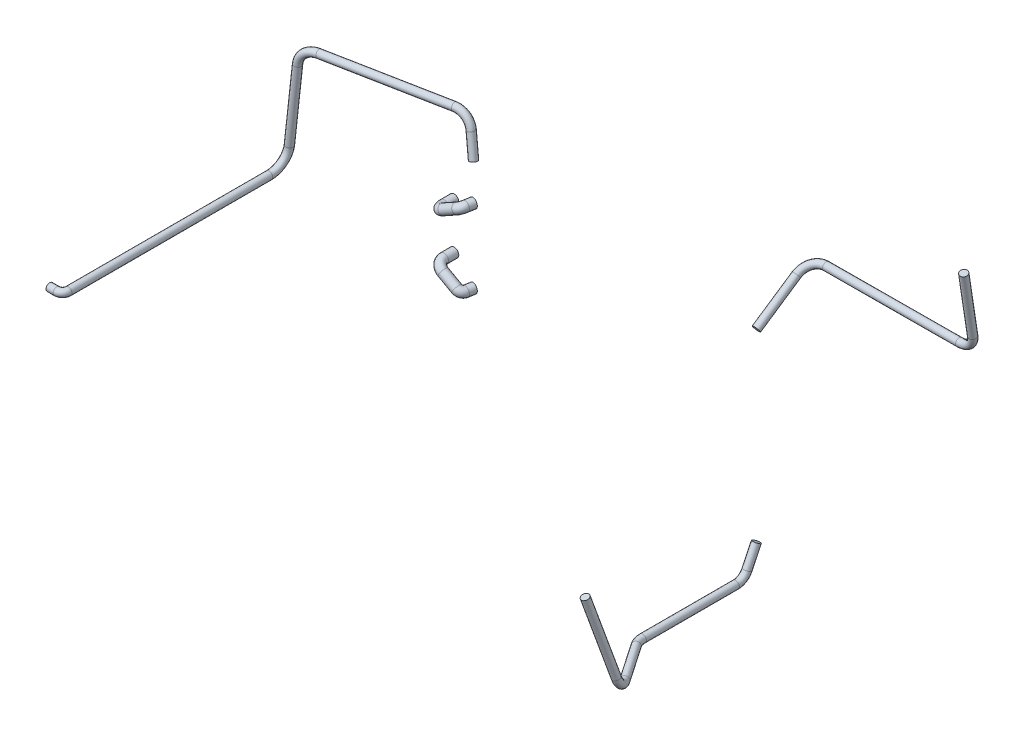
SolidWorks part; units mm, degrees
material "PVC Rigid"
ref_plane "Front Plane" through (0, 0, 0) normal (0, 0, 1) x (1, 0, 0)
ref_plane "Top Plane" through (0, 0, 0) normal (0, 1, 0) x (1, 0, 0)
ref_plane "Right Plane" through (0, 0, 0) normal (1, 0, 0) x (0, 0, -1)
sketch3d "Pipe path 1"
  line L0 (300, 25, 337) -> (300, 25, 348)
  line L1 (307.8674, 29.3708, 357) -> (322.8592, 37.6996, 357)
  line L2 (327.7787, 40, 352.3275) -> (329, 40, 345)
  arc A0 (300, 25, 348) -> (307.8674, 29.3708, 357) centre (307.8674, 29.3708, 348) ccw
  arc A1 (322.8592, 37.6996, 357) -> (327.7787, 40, 352.3275) centre (323.0737, 37.3135, 351.5434) ccw
  point P6 (300, 25, 357)
  point P7 (303.4966, 37.2382, 348)
  point P10 (327, 40, 357)
  point P11 (320.4237, 42.0834, 351.1017)
  dimension "D1" = 9
  dimension "D2" = 5.4745
sweep "Pipe 1" add path "Pipe path 1" circular profile diameter 10 parameters "D3"=10
sketch3d "Pipe path 2"
  line L0 (300, -25, 337) -> (300, -25, 348)
  line L1 (307.8674, -29.3708, 357) -> (322.8592, -37.6996, 357)
  line L2 (327.7787, -40, 352.3275) -> (329, -40, 345)
  arc A0 (300, -25, 348) -> (307.8674, -29.3708, 357) centre (307.8674, -29.3708, 348) ccw
  arc A1 (322.8592, -37.6996, 357) -> (327.7787, -40, 352.3275) centre (323.0737, -37.3135, 351.5434) ccw
  point P6 (300, -25, 357)
  point P7 (312.2382, -21.5034, 348)
  point P10 (327, -40, 357)
  point P11 (325.7237, -32.5435, 351.985)
  dimension "D1" = 9
  dimension "D2" = 5.4745
sweep "Pipe 2" add path "Pipe path 2" circular profile diameter 10 parameters "D3"=10
sketch3d "Pipe path 3"
  line L0 (138, 0, 614) -> (145.7, 0, 614)
  line L1 (152, 0, 607.7) -> (152, 0, 390)
  line L2 (154.1901, 19.8797, 370) -> (163.0339, 100.1541, 370)
  line L3 (182.6267, 118, 366.5884) -> (305.8026, 118, 342.7479)
  line L4 (323.3058, 104.0423, 341.8365) -> (329, 80, 345)
  arc A0 (145.7, 0, 614) -> (152, 0, 607.7) centre (145.7, 0, 607.7) ccw
  arc A1 (152, 0, 390) -> (154.1901, 19.8797, 370) centre (154.1901, 19.8797, 390) ccw
  arc A2 (163.0339, 100.1541, 370) -> (182.6267, 118, 366.5884) centre (182.5472, 98.0044, 366.1774) ccw
  arc A3 (305.8026, 118, 342.7479) -> (323.3058, 104.0423, 341.8365) centre (306.3803, 100.5463, 345.7327) ccw
  point P8 (152, 0, 614)
  point P9 (145.7, 6.3, 607.7)
  point P12 (152, 0, 370)
  point P13 (174.0699, 17.6896, 390)
  point P16 (165, 118, 370)
  point P17 (178.7476, 98.423, 346.5461)
  point P20 (320, 118, 340)
  point P21 (303.0637, 97.5061, 328.597)
  dimension "D1" = 6.3
  dimension "D2" = 20
  dimension "D3" = 20
  dimension "D4" = 17.7165
sweep "Pipe 3" add path "Pipe path 3" circular profile diameter 8 parameters "D3"=8
sketch3d "Pipe path 4"
  line L0 (690, -30, 584.8649) -> (698.5419, -113.7105, 559.7471)
  line L1 (691.5272, -128, 543.0938) -> (665.1512, -128, 504.5991)
  line L2 (662, -128, 494.4249) -> (662, -128, 393.5653)
  line L3 (661.7305, -120.4536, 380.9573) -> (661, -100, 370)
  arc A0 (698.5419, -113.7105, 559.7471) -> (691.5272, -128, 543.0938) centre (687.8747, -110.5531, 545.5964) ccw
  arc A1 (665.1512, -128, 504.5991) -> (662, -128, 494.4249) centre (680, -128, 494.4249) ccw
  arc A2 (662, -128, 393.5653) -> (661.7305, -120.4536, 380.9573) centre (661.4896, -113.7079, 393.5653) ccw
  point P7 (700, -128, 555.4595)
  point P8 (702.2673, -106.1254, 535.7349)
  point P11 (662, -128, 500)
  point P12 (680, -146, 494.4249)
  point P15 (662, -128, 385)
  point P16 (675.7817, -113.1975, 393.5653)
  dimension "D1" = 18
  dimension "D2" = 18
  dimension "D3" = 14.3012
sweep "Pipe 4" add path "Pipe path 4" circular profile diameter 8 parameters "D3"=8
sketch3d "Pipe path 5"
  line L0 (846, 225, 330) -> (841.1587, 156.4155, 315.4762)
  line L1 (823.1808, 140, 312.0945) -> (679.6617, 140, 312.9008)
  line L2 (661.7464, 129.8556, 327.4558) -> (661, 100, 370)
  arc A0 (841.1587, 156.4155, 315.4762) -> (823.1808, 140, 312.0945) centre (823.2018, 157.6081, 315.8301) ccw
  arc A1 (679.6617, 140, 312.9008) -> (661.7464, 129.8556, 327.4558) centre (679.7444, 129.6595, 327.634) ccw
  point P6 (840, 140, 312)
  point P7 (823.1029, 161.3438, 298.2223)
  point P10 (662, 140, 313)
  point P11 (679.8025, 144.393, 337.9743)
  dimension "D1" = 18
  dimension "D2" = 18
sweep "Pipe 5" add path "Pipe path 5" circular profile diameter 8 parameters "D3"=8
